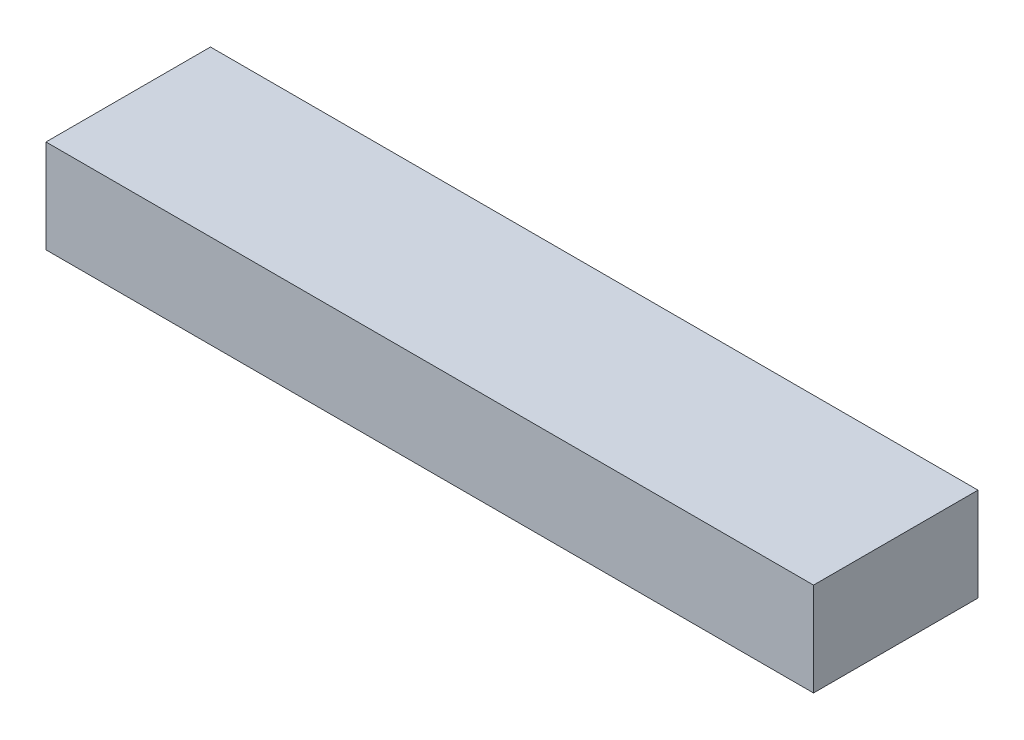
SolidWorks part; units mm, degrees
ref_plane "Front Plane" through (0, 0, 0) normal (0, 0, 1) x (1, 0, 0)
ref_plane "Top Plane" through (0, 0, 0) normal (0, 1, 0) x (1, 0, 0)
ref_plane "Right Plane" through (0, 0, 0) normal (1, 0, 0) x (0, 0, -1)
sketch "Sketch1" plane through (0, 0, 0) normal (0, 0, 1) x (1, 0, 0)
  line L0 (0, 0) -> (0, 43.2998)
  line L1 (0, 43.2998) -> (355.6, 43.2998)
  line L2 (355.6, 43.2998) -> (355.6, 0)
  line L3 (355.6, 0) -> (0, 0)
  dimension "D1" = 43.2998
  dimension "D2" = 355.6
extrude "Boss-Extrude1" add sketch "Sketch1" along normal blind 76.2
